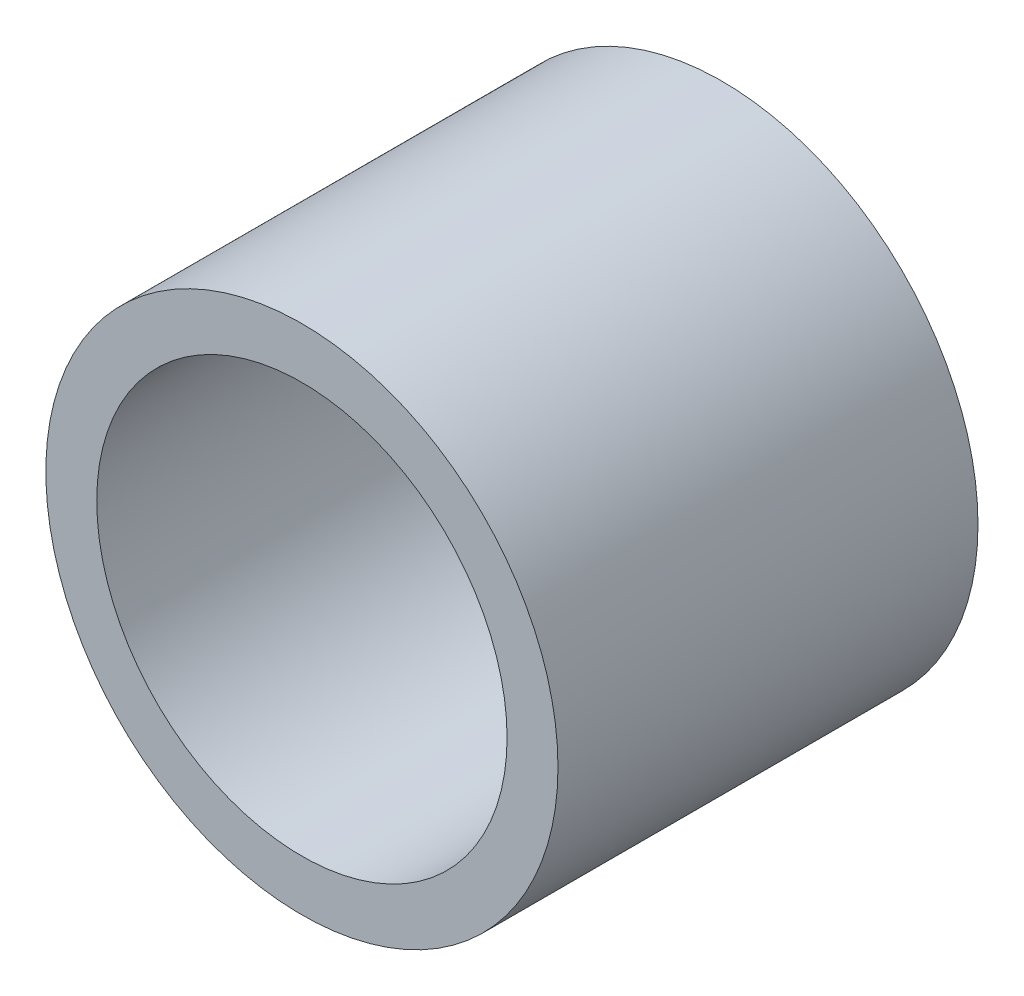
SolidWorks part; units mm, degrees
ref_plane "Front Plane" through (0, 0, 0) normal (0, 0, 1) x (1, 0, 0)
ref_plane "Top Plane" through (0, 0, 0) normal (0, 1, 0) x (1, 0, 0)
ref_plane "Right Plane" through (0, 0, 0) normal (1, 0, 0) x (0, 0, -1)
sketch "Sketch1" plane through (0, 0, 0) normal (0, 0, 1) x (1, 0, 0)
  circle A0 centre (0, 0) radius 4.03
  dimension "D1" = 8.06
extrude "Extrude-Thin1" add sketch "Sketch1" along normal blind 8.25 thin
